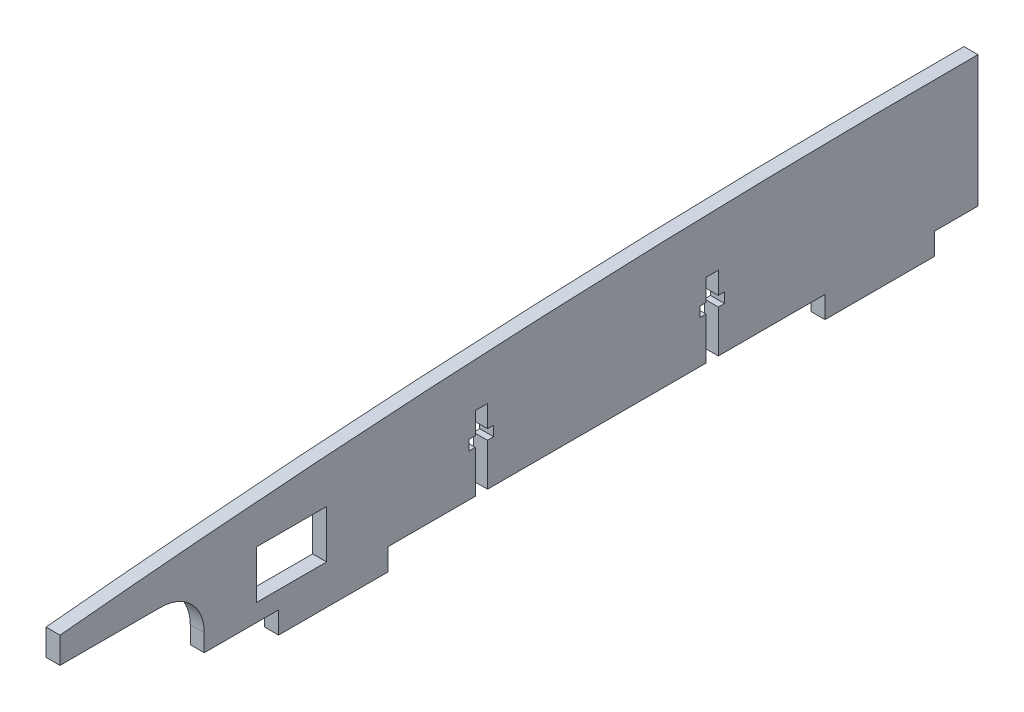
SolidWorks part; units mm, degrees
ref_plane "Front Plane" through (0, 0, 0) normal (0, 0, 1) x (1, 0, 0)
ref_plane "Top Plane" through (0, 0, 0) normal (0, 1, 0) x (1, 0, 0)
ref_plane "Right Plane" through (0, 0, 0) normal (1, 0, 0) x (0, 0, -1)
sketch "Sketch1" plane through (0, 0, 0) normal (1, 0, 0) x (0, 0, -1)
  line L0 (-87.5354, 0) -> (122.4646, 0)
  line L1 (122.4646, 0) -> (122.4646, 30)
  line L2 (-87.5354, 0) -> (-87.5354, 20)
  line L3 (122.4646, 30) -> (8.5435, 30) construction
  spline S0 degree 2 poles (-87.5354, 20) (17.331, 30.2969) (122.4646, 30) knots 0 0 0 1 1 1
  point P11 (110.6793, 30)
  dimension "D1" = 210
  dimension "D2" = 30
  dimension "D3" = 20
extrude "main" add sketch "Sketch1" along normal blind 3.2
sketch "Sketch2" plane through (3.2, 0, 0) normal (1, 0, 0) x (0, 0, -1)
  line L3 (-87.5354, 0) -> (-54.5354, 0)
  line L4 (-87.5354, 0) -> (-87.5354, 14)
  line L5 (-87.5354, 14) -> (-64.5354, 14)
  line L6 (-54.5354, 0) -> (-54.5354, 4)
  arc A1 (-54.5354, 4) -> (-64.5354, 14) centre (-64.5354, 4) ccw
  dimension "D1" = 10
  dimension "D2" = 33
  dimension "D3" = 14
extrude "wheel" cut sketch "Sketch2" against normal blind 3.2
sketch "Sketch3" plane through (3.2, 0, 0) normal (1, 0, 0) x (0, 0, -1)
  line L0 (-54.5354, 0) -> (122.4646, 0) construction
  line L1 (-37.5354, 0) -> (-12.5354, 0)
  line L2 (-37.5354, 0) -> (-37.5354, -5)
  line L3 (-37.5354, -5) -> (-12.5354, -5)
  line L4 (-12.5354, 0) -> (-12.5354, -5)
  line L5 (87.4646, 0) -> (87.4646, -5)
  line L6 (87.4646, 0) -> (112.4646, 0)
  line L7 (112.4646, 0) -> (112.4646, -5)
  line L8 (87.4646, -5) -> (112.4646, -5)
  line L9 (-87.5354, 20) -> (-87.5354, 14) construction
  dimension "D2" = 25
  dimension "D3" = 5
  dimension "D4" = 50
  dimension "D5" = 100
  dimension "D1" = 2
extrude "tabs" add sketch "Sketch3" against normal up to surface (3.2 mm away) up to face at (0, 12.7244, -0.4747)
sketch "Sketch5" plane through (3.2, 0, 0) normal (1, 0, 0) x (0, 0, -1)
  line L0 (-12.5354, 0) -> (87.4646, 0) construction
  line L1 (7.4646, 0) -> (10.2646, 0)
  line L2 (7.4646, 0) -> (7.4646, 9.7)
  line L3 (7.4646, 17) -> (10.2646, 17)
  line L4 (10.2646, 0) -> (10.2646, 9.7)
  line L5 (7.4646, 12) -> (7.4646, 17)
  line L6 (6.0646, 12) -> (7.4646, 12)
  line L7 (6.0646, 12) -> (6.0646, 9.7)
  line L8 (6.0646, 9.7) -> (7.4646, 9.7)
  line L9 (11.6646, 12) -> (11.6646, 9.7)
  line L10 (10.2646, 12) -> (11.6646, 12)
  line L11 (10.2646, 12) -> (10.2646, 17)
  line L12 (10.2646, 9.7) -> (11.6646, 9.7)
  line L13 (60.2646, 0) -> (63.0646, 0)
  line L14 (60.2646, 0) -> (60.2646, 9.7)
  line L15 (60.2646, 17) -> (63.0646, 17)
  line L16 (63.0646, 0) -> (63.0646, 9.7)
  line L17 (60.2646, 12) -> (60.2646, 17)
  line L18 (58.8646, 12) -> (60.2646, 12)
  line L19 (58.8646, 12) -> (58.8646, 9.7)
  line L20 (58.8646, 9.7) -> (60.2646, 9.7)
  line L21 (64.4646, 12) -> (64.4646, 9.7)
  line L22 (63.0646, 12) -> (64.4646, 12)
  line L23 (63.0646, 12) -> (63.0646, 17)
  line L24 (63.0646, 9.7) -> (64.4646, 9.7)
  line L25 (-12.5354, -5) -> (-12.5354, 0) construction
  dimension "D1" = 2.3
  dimension "D2" = 2.8
  dimension "D3" = 5
  dimension "D4" = 17
  dimension "D6" = 20
  dimension "D7" = 5.6
  dimension "D8" = 50
  dimension "D5" = 2
extrude "screw holes" cut sketch "Sketch5" against normal up to surface (3.2 mm away) up to face at (0, 4.6047, -20.2026)
sketch "Sketch6" plane through (3.2, 0, 0) normal (1, 0, 0) x (0, 0, -1)
  line L0 (-54.5354, 0) -> (-37.5354, 0) construction
  line L1 (-42.5354, 15) -> (-26.5354, 15)
  line L2 (-42.5354, 15) -> (-42.5354, 4)
  line L3 (-42.5354, 4) -> (-26.5354, 4)
  line L4 (-26.5354, 15) -> (-26.5354, 4)
  dimension "D1" = 11
  dimension "D2" = 16
  dimension "D3" = 12
  dimension "D4" = 4
extrude "USB hole" cut sketch "Sketch6" against normal up to surface (3.2 mm away) up to face at (0, 7.9659, -29.4715)
